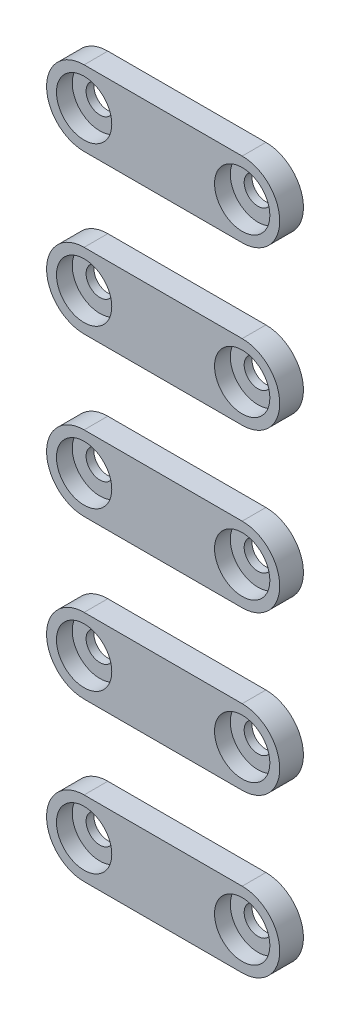
SolidWorks part; units mm, degrees
ref_plane "Front Plane" through (0, 0, 0) normal (0, 0, 1) x (1, 0, 0)
ref_plane "Top Plane" through (0, 0, 0) normal (0, 1, 0) x (1, 0, 0)
ref_plane "Right Plane" through (0, 0, 0) normal (1, 0, 0) x (0, 0, -1)
sketch "Sketch1" plane through (0, 0, -1) normal (0, 0, 1) x (1, 0, 0)
  line L0 (10, 0) -> (-10, 0) construction
  line L1 (10, -4.75) -> (-10, -4.75)
  line L2 (10, 4.75) -> (-10, 4.75)
  line L4 (10, 20) -> (-10, 20) construction
  line L5 (10, 15.25) -> (-10, 15.25)
  line L6 (10, 24.75) -> (-10, 24.75)
  line L7 (10, 40) -> (-10, 40) construction
  line L8 (10, 35.25) -> (-10, 35.25)
  line L9 (10, 44.75) -> (-10, 44.75)
  line L10 (10, -20) -> (-10, -20) construction
  line L11 (10, -24.75) -> (-10, -24.75)
  line L12 (10, -15.25) -> (-10, -15.25)
  line L13 (10, -40) -> (-10, -40) construction
  line L14 (10, -44.75) -> (-10, -44.75)
  line L15 (10, -35.25) -> (-10, -35.25)
  arc A0 (10, -4.75) -> (10, 4.75) centre (10, 0) ccw
  arc A1 (-10, 4.75) -> (-10, -4.75) centre (-10, 0) ccw
  arc A5 (10, 15.25) -> (10, 24.75) centre (10, 20) ccw
  arc A6 (-10, 24.75) -> (-10, 15.25) centre (-10, 20) ccw
  arc A7 (10, 35.25) -> (10, 44.75) centre (10, 40) ccw
  arc A8 (-10, 44.75) -> (-10, 35.25) centre (-10, 40) ccw
  arc A9 (10, -24.75) -> (10, -15.25) centre (10, -20) ccw
  arc A10 (-10, -15.25) -> (-10, -24.75) centre (-10, -20) ccw
  arc A11 (10, -44.75) -> (10, -35.25) centre (10, -40) ccw
  arc A12 (-10, -35.25) -> (-10, -44.75) centre (-10, -40) ccw
  point P2 (0, 0)
  point P14 (14.75, 0)
  point P15 (0, 0)
  point P16 (0, 0)
  point P19 (0, 20)
  point P26 (0, 40)
  point P33 (0, -20)
  point P40 (0, -40)
  dimension "D3" = 3
  dimension "D4" = 20
  dimension "D6" = 20
  dimension "D5" = 3
extrude "Boss-Extrude1" add sketch "Sketch1" along normal blind 3
sketch "Sketch2" plane through (0, 0, 2) normal (0, 0, 1) x (1, 0, 0)
  line L0 (0, 44.75) -> (0, 35.25) construction
  line L1 (10, 44.75) -> (-10, 44.75) construction
  line L2 (-10, 35.25) -> (10, 35.25) construction
  circle A0 centre (-10, 40) radius 1.75
  circle A1 centre (10, 40) radius 1.75
  circle A2 centre (-10, 20) radius 1.75
  circle A3 centre (10, 20) radius 1.75
  circle A4 centre (-10, 0) radius 1.75
  circle A5 centre (10, 0) radius 1.75
  circle A6 centre (-10, -20) radius 1.75
  circle A7 centre (10, -20) radius 1.75
  circle A8 centre (-10, -40) radius 1.75
  circle A9 centre (10, -40) radius 1.75
  point P9 (0, 40)
  dimension "D2" = 3.5
  dimension "D1" = 10
  dimension "D4" = 20
  dimension "D3" = 5
extrude "Cut-Extrude1" cut sketch "Sketch2" against normal up to surface (3 mm away) up to face at (0, 40, -1)
sketch "Sketch3" plane through (0, 0, 2) normal (0, 0, 1) x (1, 0, 0)
  circle A0 centre (-10, 40) radius 3.5
  circle A1 centre (10, 40) radius 3.5
  circle A2 centre (-10, 20) radius 3.5
  circle A3 centre (10, 20) radius 3.5
  circle A4 centre (-10, 0) radius 3.5
  circle A5 centre (10, 0) radius 3.5
  circle A6 centre (-10, -20) radius 3.5
  circle A7 centre (10, -20) radius 3.5
  circle A8 centre (-10, -40) radius 3.5
  circle A9 centre (10, -40) radius 3.5
  dimension "D1" = 7
  dimension "D2" = 7
  dimension "D4" = 20
  dimension "D3" = 5
extrude "Cut-Extrude2" cut sketch "Sketch3" against normal blind 2
